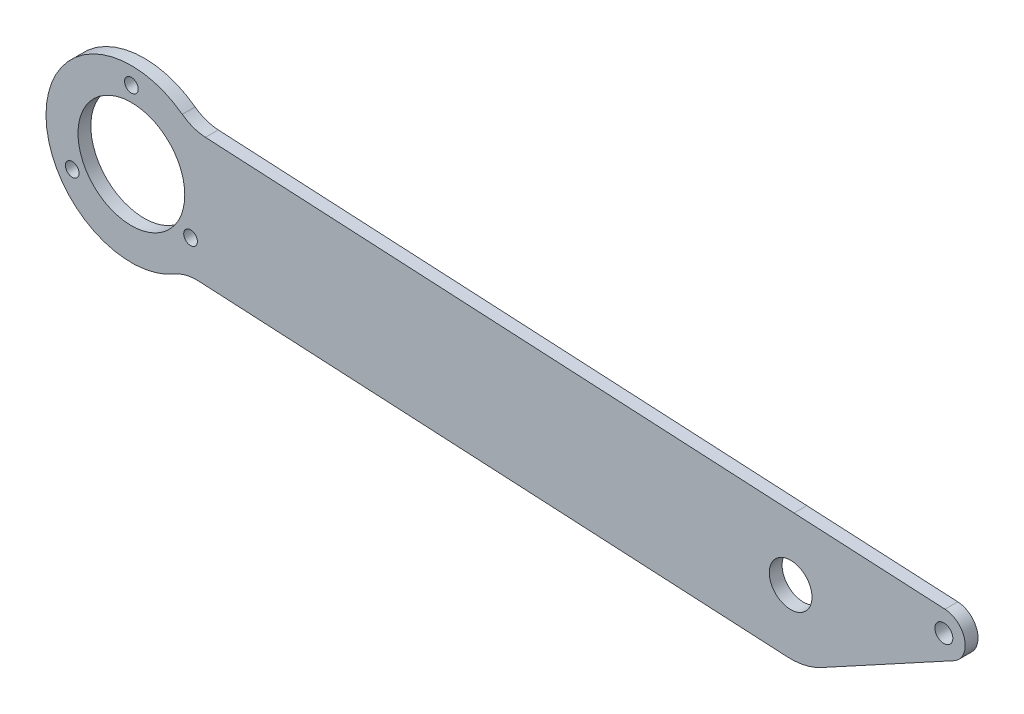
SolidWorks part; units mm, degrees
material "氧化铝"
ref_plane "前视基准面" through (0, 0, 0) normal (0, 0, 1) x (1, 0, 0)
ref_plane "上视基准面" through (0, 0, 0) normal (0, 1, 0) x (1, 0, 0)
ref_plane "右视基准面" through (0, 0, 0) normal (1, 0, 0) x (0, 0, -1)
sketch "草图1" plane through (0, 0, 0) normal (0, 0, 1) x (1, 0, 0)
  line L0 (0, 0) -> (190.28, 0) construction
  line L1 (190.28, 0) -> (154.3948, -8.1544) construction
  line L2 (154.3948, -8.1544) -> (0, 0) construction
  line L3 (12.4192, -15.6768) -> (153.6037, -23.1335)
  line L4 (161.5683, -21.3279) -> (192.6712, -4.3912)
  line L5 (14.0015, 14.2814) -> (155.1859, 6.8248)
  line L6 (190.5387, 4.9933) -> (155.1859, 6.8248)
  arc A0 (14.0015, 14.2814) -> (12.4192, -15.6768) centre (0, 0) ccw
  circle A1 centre (154.3948, -8.1544) radius 5
  circle A2 centre (190.28, 0) radius 2.1
  arc A3 (153.6037, -23.1335) -> (161.5683, -21.3279) centre (154.3948, -8.1544) ccw
  arc A4 (192.6712, -4.3912) -> (190.5387, 4.9933) centre (190.28, 0) ccw
  circle A7 centre (0, 0) radius 16 construction
  circle A9 centre (0, 16) radius 1.6
  circle A15 centre (0, 0) radius 12.5
  circle A18 centre (13.8564, -8) radius 1.6
  circle A19 centre (0, 0) radius 16 construction
  circle A20 centre (-13.8564, -8) radius 1.6
  circle A21 centre (0, 0) radius 16 construction
  point P27 (0, 0)
  point P30 (0, 0)
  point P31 (0, 0)
  point P38 (0, 0)
  dimension "D4" = 40
  dimension "D6" = 10
  dimension "D7" = 4.2
  dimension "D8" = 10
  dimension "D9" = 25
  dimension "D11" = 32
  dimension "D13" = 3.2
  dimension "D1" = 190.28
  dimension "D2" = 154.61
  dimension "D3" = 36.8
  dimension "D5" = 15
  dimension "D15" = 3
extrude "凸台-拉伸1" add sketch "草图1" along normal blind 3
fillet "圆角1" radius 10 1 edges at (14.0015, 14.2814, 1.5)
fillet "圆角2" radius 10 1 edges at (12.4192, -15.6768, 1.5)
